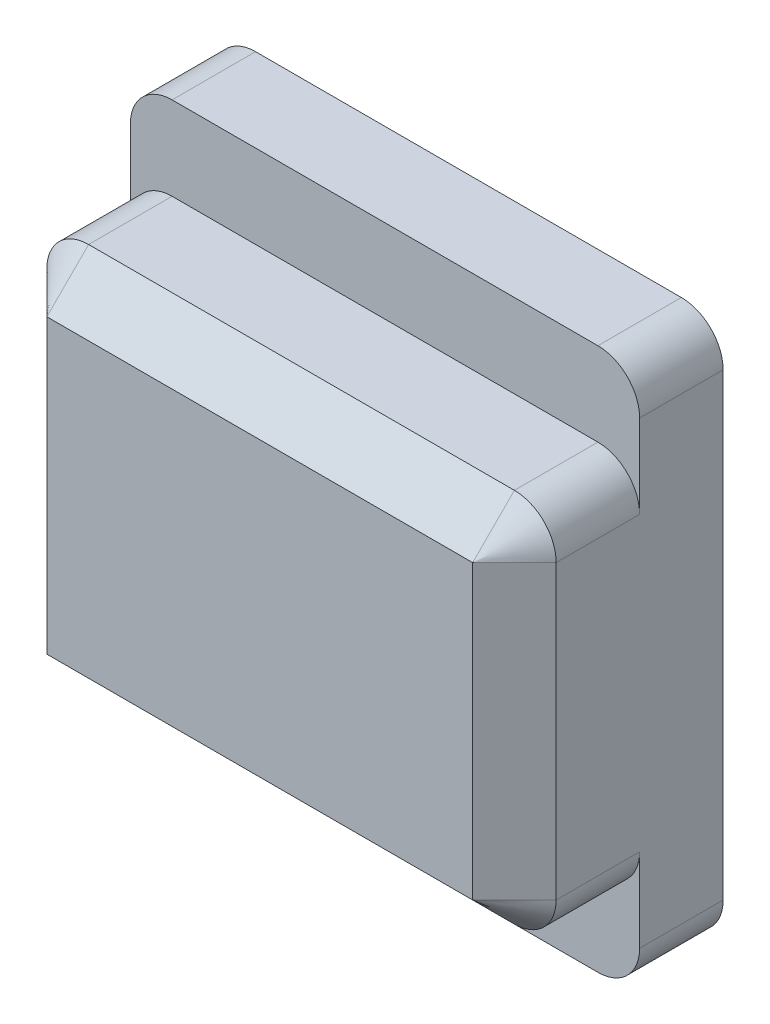
SolidWorks part; units mm, degrees
ref_plane "前视基准面" through (0, 0, 0) normal (0, 0, 1) x (1, 0, 0)
ref_plane "上视基准面" through (0, 0, 0) normal (0, 1, 0) x (1, 0, 0)
ref_plane "右视基准面" through (0, 0, 0) normal (1, 0, 0) x (0, 0, -1)
sketch "草图1" plane through (0, 0, 0) normal (0, 0, 1) x (1, 0, 0)
  line L3 (-9.15, -1.25) -> (-9.15, -3.45) construction
  line L4 (7.9, 0) -> (-7.9, 0) construction
  line L5 (9.15, -3.45) -> (9.15, -1.25) construction
  line L6 (-7.9, -4.7) -> (7.9, -4.7) construction
  line L7 (-9.05, -1.25) -> (-9.05, -3.45)
  line L8 (-7.9, -4.6) -> (7.9, -4.6)
  line L9 (9.05, -3.45) -> (9.05, -1.25)
  line L10 (7.9, -0.1) -> (-7.9, -0.1)
  arc A2 (-7.9, 0) -> (-9.15, -1.25) centre (-7.9, -1.25) ccw construction
  arc A3 (9.15, -1.25) -> (7.9, 0) centre (7.9, -1.25) ccw construction
  arc A4 (9.15, -3.45) -> (7.9, -4.7) centre (7.9, -3.45) cw construction
  arc A5 (-7.9, -4.7) -> (-9.15, -3.45) centre (-7.9, -3.45) cw construction
  arc A6 (-7.9, -4.6) -> (-9.05, -3.45) centre (-7.9, -3.45) cw
  arc A7 (9.05, -3.45) -> (7.9, -4.6) centre (7.9, -3.45) cw
  arc A8 (9.05, -1.25) -> (7.9, -0.1) centre (7.9, -1.25) ccw
  arc A9 (-7.9, -0.1) -> (-9.05, -1.25) centre (-7.9, -1.25) ccw
  dimension "D1" = 1.25
  dimension "D2" = 0.1
extrude "凸台-拉伸1" add sketch "草图1" against normal blind 2.5
sketch "草图2" plane through (0, 0, -2.5) normal (0, 0, -1) x (-1, 0, 0)
  line L0 (0, -0.1) -> (0, -4.6) construction
  line L1 (-7.9, -0.1) -> (7.9, -0.1) construction
  line L2 (7.9, -4.6) -> (-7.9, -4.6) construction
  line L4 (-7.9, 0.9) -> (7.9, 0.9)
  line L5 (-7.9, 0.9) -> (-7.9, -5.6)
  line L6 (-7.9, -5.6) -> (7.9, -5.6)
  line L7 (7.9, 0.9) -> (7.9, -5.6)
  line L8 (-7.9, 0.9) -> (7.9, -5.6) construction
  line L9 (-7.9, -5.6) -> (7.9, 0.9) construction
  point P6 (0, -2.35)
  dimension "D1" = 1
extrude "凸台-拉伸2" add sketch "草图2" against normal blind 1
fillet "圆角1" radius 0.5 4 edges at (-7.9, 0.9, -2) (7.9, 0.9, -2) (-7.9, -5.6, -2) (7.9, -5.6, -2)
sketch "草图3" plane through (0, 0.9, 0) normal (0, 1, 0) x (1, 0, 0)
  line L0 (8.475, 2.5) -> (9.05, 1.925)
  line L1 (9.05, 1.925) -> (9.05, 2.5)
  line L2 (9.05, 2.5) -> (8.475, 2.5)
  line L3 (0, 0) -> (0, 4.9184) construction
  line L5 (9.05, 2.5) -> (9.05, 0) construction
  line L6 (-9.05, 1.925) -> (-9.05, 2.5)
  line L7 (-8.475, 2.5) -> (-9.05, 1.925)
  line L8 (-9.05, 2.5) -> (-8.475, 2.5)
  line L9 (9.05, 2.5) -> (7.9, 2.5) construction
  dimension "D1" = 45
extrude "切除-拉伸1" cut sketch "草图3" against normal through all
sketch "草图4" plane through (0, 0, -2.5) normal (0, 0, -1) x (-1, 0, 0)
  line L0 (0, 0.9) -> (0, -5.6) construction
  line L1 (7.4, 0.9) -> (-7.4, 0.9) construction
  line L2 (-7.4, -5.6) -> (7.4, -5.6) construction
  line L4 (3.05, -5.6) -> (-3.05, -5.6)
  line L5 (3.05, -5.6) -> (3.05, 0.9)
  line L6 (3.05, 0.9) -> (-3.05, 0.9)
  line L7 (-3.05, -5.6) -> (-3.05, 0.9)
  line L8 (3.05, -5.6) -> (-3.05, 0.9) construction
  line L9 (3.05, 0.9) -> (-3.05, -5.6) construction
  line L10 (10.7797, -8.7954) -> (-10.7797, -8.7954)
  line L11 (10.7797, -8.7954) -> (10.7797, 4.0954)
  line L12 (10.7797, 4.0954) -> (-10.7797, 4.0954)
  line L13 (-10.7797, -8.7954) -> (-10.7797, 4.0954)
  line L14 (10.7797, -8.7954) -> (-10.7797, 4.0954) construction
  line L15 (10.7797, 4.0954) -> (-10.7797, -8.7954) construction
  point P6 (0, -2.35)
  point P11 (0, -2.35)
  dimension "D1" = 6.1
extrude "切除-拉伸2" cut sketch "草图4" against normal blind 10 contours L11 L10 L13 L12 | L4 L7 L6 L5
fillet "圆角2" radius 0.5 8 edges at (-3.05, -4.6, -0.75) (3.05, -5.6, -2) (-3.05, -5.6, -2) (3.05, -4.6, -0.75) (-3.05, 0.9, -2) (3.05, 0.9, -2) (-3.05, -0.1, -0.75) (3.05, -0.1, -0.75)
chamfer "倒角1" distance 0.5 angle 45 8 edges at (0, -4.6, 0) (0, -0.1, 0) (-2.9036, -0.2464, 0) (2.9036, -0.2464, 0) (3.05, -2.35, 0) (2.9036, -4.4536, 0) (-2.9036, -4.4536, 0) (-3.05, -2.35, 0)
